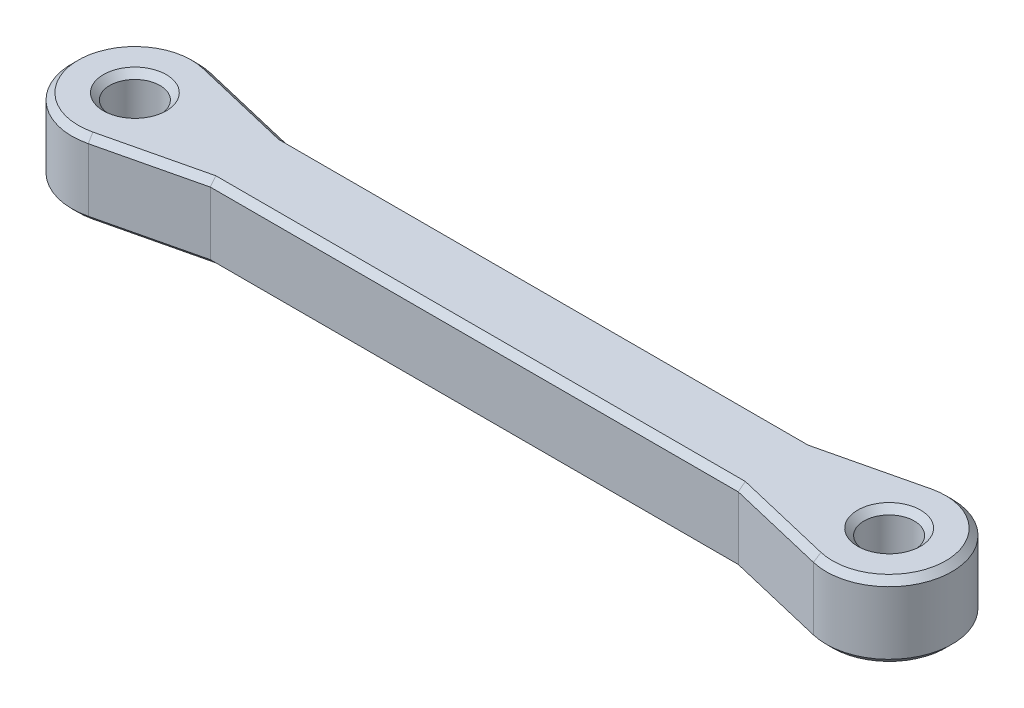
SolidWorks part; units mm, degrees
ref_plane "前视基准面" through (0, 0, 0) normal (0, 0, 1) x (1, 0, 0)
ref_plane "上视基准面" through (0, 0, 0) normal (0, 1, 0) x (1, 0, 0)
ref_plane "右视基准面" through (0, 0, 0) normal (1, 0, 0) x (0, 0, -1)
other "Configuration Table"
sketch "草图1" plane through (0, 0, 0) normal (0, 1, 0) x (1, 0, 0)
  line L0 (0, 0) -> (30, 0) construction
  line L1 (2, 1.5) -> (28, 1.5)
  line L2 (28, -1.5) -> (2, -1.5)
  arc A0 (2, 1.5) -> (2, -1.5) centre (0, 0) ccw
  arc A1 (28, -1.5) -> (28, 1.5) centre (30, 0) ccw
  dimension "D1" = 5
  dimension "D3" = 5
  dimension "D2" = 30
  dimension "D4" = 3
extrude "凸台-拉伸1" add sketch "草图1" along normal blind 3
sketch "草图2" plane through (0, 0, 0) normal (0, 1, 0) x (1, 0, 0)
  circle A0 centre (0, 0) radius 1
  circle A1 centre (30, 0) radius 1
  dimension "D1" = 2
  dimension "D2" = 2
extrude "切除-拉伸1" cut sketch "草图2" along normal up to surface (3 mm away) up to face at (15, 3, 0)
sketch "草图3" plane through (0, 0, 0) normal (0, 1, 0) x (1, 0, 0)
  line L0 (4.5, 1.5) -> (0.5781, 2.4322)
  line L1 (4.5, -1.5) -> (0.5781, -2.4322)
  line L2 (2, -1.5) -> (28, -1.5)
  line L3 (28, 1.5) -> (2, 1.5)
  line L4 (2, -1.5) -> (4.5, -1.5)
  line L5 (28, 1.5) -> (25.5, 1.5)
  line L6 (25.5, 1.5) -> (29.4219, 2.4322)
  line L7 (25.5, -1.5) -> (29.4219, -2.4322)
  line L8 (25.5, -1.5) -> (28, -1.5)
  line L9 (4.5, 1.5) -> (2, 1.5)
  arc A0 (0.5781, -2.4322) -> (2, -1.5) centre (0, 0) ccw
  arc A1 (29.4219, 2.4322) -> (28, 1.5) centre (30, 0) ccw
  arc A2 (2, 1.5) -> (2, -1.5) centre (0, 0) ccw
  arc A3 (28, -1.5) -> (28, 1.5) centre (30, 0) ccw
  arc A4 (2, 1.5) -> (0.5781, 2.4322) centre (0, 0) ccw
  arc A5 (28, -1.5) -> (29.4219, -2.4322) centre (30, 0) ccw
  dimension "D2" = 2.5
  dimension "D3" = 2.5
  dimension "D4" = 2.5
  dimension "D5" = 2.5
  dimension "D1" = 0
extrude "凸台-拉伸2" add sketch "草图3" along normal up to surface (3 mm away) up to face at (0, 3, 1)
chamfer "倒角1" distance 0.25 angle 45 20 edges at (30, 0, 1) (0, 0, 1) (15, 0, -1.5) (2.5391, 3, -1.9661) (2.5391, 0, -1.9661) (-2.5, 0, 0) (2.5391, 3, 1.9661) (2.5391, 0, 1.9661) (15, 0, 1.5) (27.4609, 3, 1.9661) (27.4609, 0, 1.9661) (32.5, 0, 0) (27.4609, 3, -1.9661) (27.4609, 0, -1.9661) (30, 3, 1) (0, 3, 1) (15, 3, 1.5) (-2.5, 3, 0) (15, 3, -1.5) (32.5, 3, 0)
